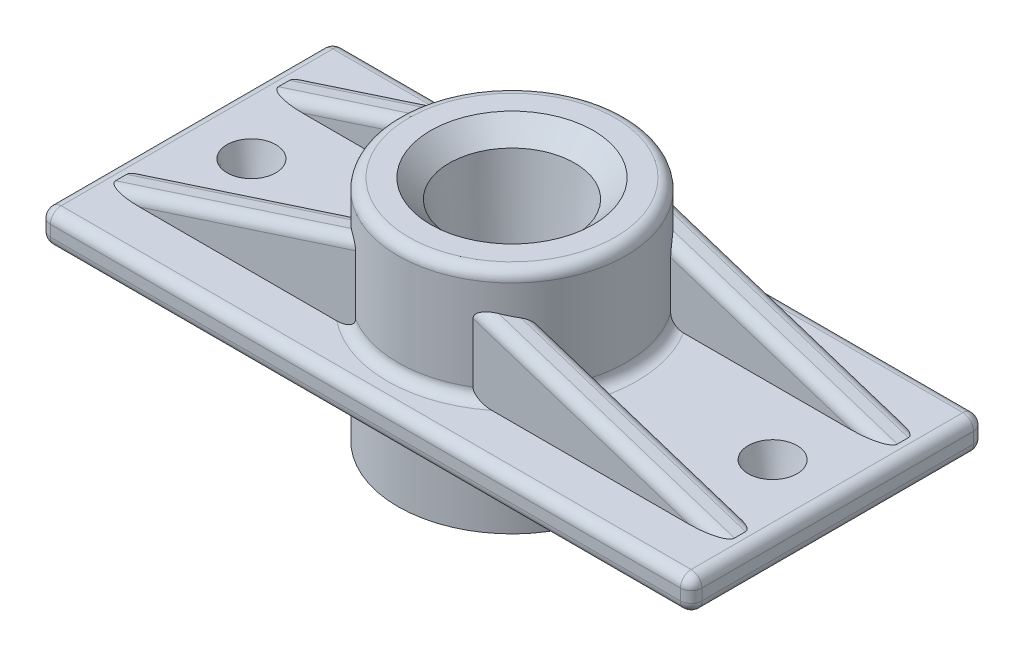
SolidWorks part; units mm, degrees
material "Cast Carbon Steel"
ref_plane "Front Plane" through (0, 0, 0) normal (0, 0, 1) x (1, 0, 0)
ref_plane "Top Plane" through (0, 0, 0) normal (0, 1, 0) x (1, 0, 0)
ref_plane "Right Plane" through (0, 0, 0) normal (1, 0, 0) x (0, 0, -1)
sketch "Sketch1" plane through (0, 0, 0) normal (0, 1, 0) x (1, 0, 0)
  line L1 (-63.5, 28.575) -> (63.5, 28.575)
  line L2 (-63.5, 28.575) -> (-63.5, -28.575)
  line L3 (-63.5, -28.575) -> (63.5, -28.575)
  line L4 (63.5, 28.575) -> (63.5, -28.575)
  line L5 (-63.5, 28.575) -> (63.5, -28.575) construction
  line L6 (-63.5, -28.575) -> (63.5, 28.575) construction
  point P0 (0, 0)
  dimension "D1" = 127
  dimension "D2" = 57.15
extrude "Boss-Extrude1" add sketch "Sketch1" along normal blind 6.35
sketch "Sketch2" plane through (0, 6.35, 0) normal (0, 1, 0) x (1, 0, 0)
  line L0 (0, 22.712) -> (0, -15.0013) construction
  line L1 (0, -3.4925) -> (0, 3.4925) construction
  line L2 (-3.4925, 0) -> (3.4925, 0) construction
  circle A0 centre (-50.8, 0) radius 4.7625
  circle A1 centre (50.8, 0) radius 4.7625
  dimension "D2" = 9.525
  dimension "D1" = 101.6
extrude "Cut-Extrude1" cut sketch "Sketch2" against normal through all draft 15
sketch "Sketch3" plane through (0, 6.35, 0) normal (0, 1, 0) x (1, 0, 0)
  circle A0 centre (0, 0) radius 22.225
  dimension "D1" = 44.45
extrude "Boss-Extrude2" add sketch "Sketch3" along normal blind 22.225 and the other way blind 22.225
sketch "Sketch4" plane through (0, 28.575, 0) normal (0, 1, 0) x (1, 0, 0)
  circle A0 centre (0, 0) radius 12.7
  dimension "D1" = 25.4
extrude "Cut-Extrude2" cut sketch "Sketch4" against normal through all draft 7.5
ref_plane "Plane1" through (0, 0, 19.05) normal (0, 0, 1) x (1, 0, 0)
sketch "Sketch5" plane through (0, 0, 19.05) normal (0, 0, 1) x (1, 0, 0)
  line L0 (0, 27.1574) -> (0, -12.5789) construction
  line L1 (0, -24.4475) -> (0, 24.4475) construction
  line L2 (11.43, 22.225) -> (11.43, 6.35)
  line L3 (-63.5, 6.35) -> (63.5, 6.35) construction
  line L4 (-11.43, 22.225) -> (-11.43, 6.35)
  line L5 (11.43, 6.35) -> (60.325, 6.35)
  line L6 (-11.43, 6.35) -> (-60.325, 6.35)
  line L7 (60.325, 6.35) -> (11.43, 22.225)
  line L8 (-60.325, 6.35) -> (-11.43, 22.225)
  line L9 (22.225, 28.575) -> (-22.225, 28.575) construction
  dimension "D1" = 22.86
  dimension "D2" = 120.65
  dimension "D3" = 6.35
extrude "Boss-Extrude3" add sketch "Sketch5" against normal blind 6.35
mirror "Mirror1" about plane through (0, 0, 0) normal (0, 0, 1) of "Boss-Extrude3"
chamfer "Chamfer1" distance 3.175 angle 45 1 edges at (0, 28.575, 12.7)
fillet "Fillet1" radius 2.0955 25 edges at (35.8863, 14.2846, 19.05) (39.282, 13.1821, 12.7) (35.8863, 14.2846, -19.05) (39.282, 13.1821, -12.7) (-39.282, 13.1821, 12.7) (-35.8863, 14.2846, 19.05) (-39.282, 13.1821, -12.7) (-35.8863, 14.2846, -19.05) (-22.225, 6.35, 0) (0, 6.35, 22.225) (22.225, 6.35, 0) (0, 6.35, -22.225) (-63.5, 6.35, 0) (-63.5, 0, 0) (0, 6.35, -28.575) (-63.5, 3.175, -28.575) (0, 0, -28.575) (63.5, 6.35, 0) (63.5, 3.175, -28.575) (63.5, 0, 0) (-63.5, 3.175, 28.575) (0, 6.35, 28.575) (63.5, 3.175, 28.575) (0, 0, 28.575) (0, 28.575, 22.225)
